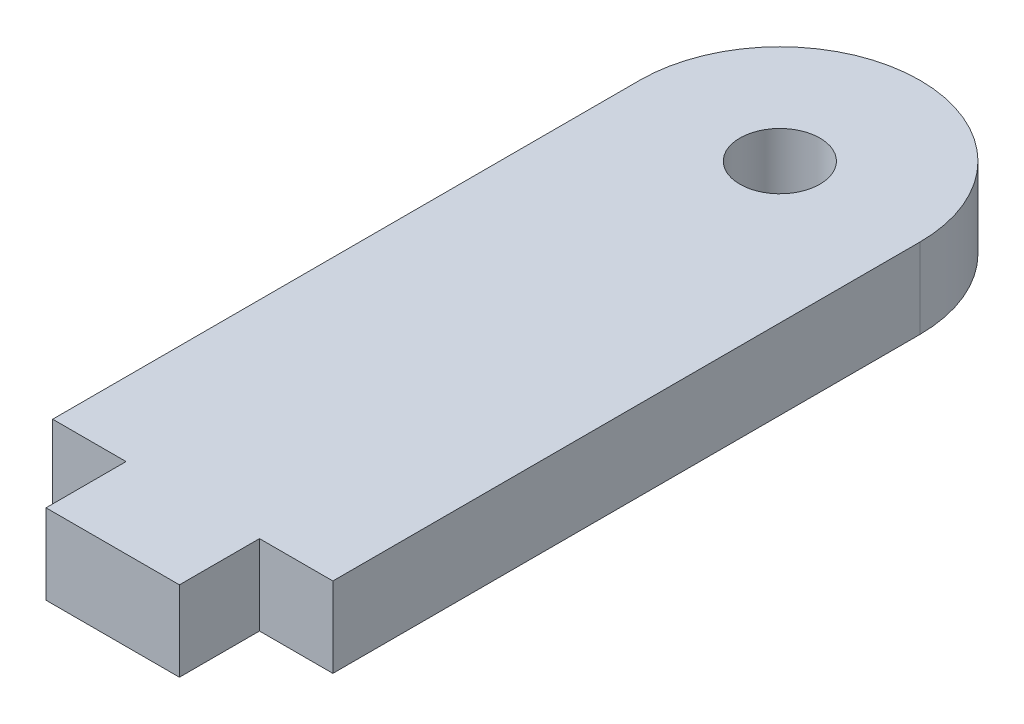
SolidWorks part; units mm, degrees
ref_plane "前视基准面" through (0, 0, 0) normal (0, 0, 1) x (1, 0, 0)
ref_plane "上视基准面" through (0, 0, 0) normal (0, 1, 0) x (1, 0, 0)
ref_plane "右视基准面" through (0, 0, 0) normal (1, 0, 0) x (0, 0, -1)
other "Configuration Table"
sketch "草图1" plane through (0, 0, 0) normal (0, 1, 0) x (1, 0, 0)
  line L1 (0, 0) -> (10.5, 0)
  line L2 (0, 0) -> (0, -22)
  line L3 (0, -22) -> (10.5, -22)
  line L4 (10.5, 0) -> (10.5, -22)
  line L5 (2.75, -22) -> (7.75, -22)
  line L6 (2.75, -22) -> (2.75, -25)
  line L7 (2.75, -25) -> (7.75, -25)
  line L8 (7.75, -22) -> (7.75, -25)
  circle A0 centre (5.25, 0) radius 5.25
  circle A1 centre (5.25, 0) radius 1.5
  dimension "D6" = 3
  dimension "D1" = 22
  dimension "D2" = 10.5
  dimension "D3" = 5
  dimension "D4" = 3
  dimension "D5" = 2.75
extrude "凸台-拉伸1" add sketch "草图1" along normal blind 3 contours A0 L2 L3 L4 | L8 L3 L6 L7 | A1 L1 A0 | A1 L1 A0
